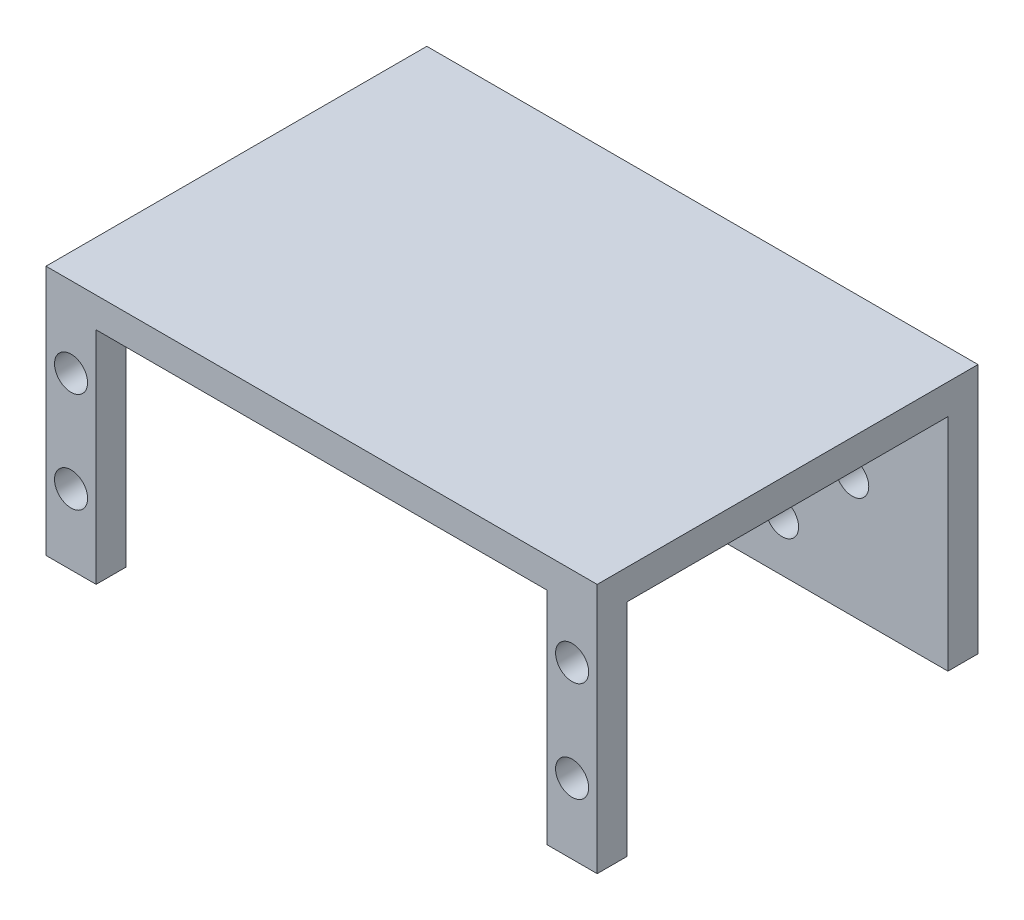
SolidWorks part; units mm, degrees
ref_plane "前视基准面" through (0, 0, 0) normal (0, 0, 1) x (1, 0, 0)
ref_plane "上视基准面" through (0, 0, 0) normal (0, 1, 0) x (1, 0, 0)
ref_plane "右视基准面" through (0, 0, 0) normal (1, 0, 0) x (0, 0, -1)
sketch "草图1" plane through (0, 0, 0) normal (0, 0, 1) x (1, 0, 0)
  line L1 (-27.5, -12.5) -> (27.5, -12.5)
  line L2 (-27.5, -12.5) -> (-27.5, 12.5)
  line L3 (-27.5, 12.5) -> (27.5, 12.5)
  line L4 (27.5, -12.5) -> (27.5, 12.5)
  line L5 (-27.5, -12.5) -> (27.5, 12.5) construction
  line L6 (-27.5, 12.5) -> (27.5, -12.5) construction
  point P0 (0, 0)
  dimension "D1" = 55
  dimension "D2" = 25
extrude "凸台-拉伸1" add sketch "草图1" along normal blind 3
sketch "草图2" plane through (0, 0, 3) normal (0, 0, 1) x (1, 0, 0)
  line L0 (27.5, -12.5) -> (27.5, 12.5) construction
  line L1 (-27.5, 12.5) -> (27.5, 12.5)
  line L2 (-27.5, 12.5) -> (-27.5, 9.5)
  line L3 (-27.5, 9.5) -> (27.5, 9.5)
  line L4 (27.5, 12.5) -> (27.5, 9.5)
  dimension "D1" = 3
extrude "凸台-拉伸2" add sketch "草图2" along normal blind 35
sketch "草图3" plane through (0, 9.5, 0) normal (0, -1, 0) x (1, 0, 0)
  line L1 (-27.5, 38) -> (-22.5, 38)
  line L2 (-27.5, 38) -> (-27.5, 35)
  line L3 (-27.5, 35) -> (-22.5, 35)
  line L4 (-22.5, 38) -> (-22.5, 35)
  line L5 (27.5, 38) -> (22.5, 38)
  line L6 (27.5, 38) -> (27.5, 35)
  line L7 (27.5, 35) -> (22.5, 35)
  line L8 (22.5, 38) -> (22.5, 35)
  dimension "D1" = 5
  dimension "D2" = 5
  dimension "D3" = 3
  dimension "D4" = 3
extrude "凸台-拉伸3" add sketch "草图3" along normal blind 22
sketch "草图4" plane through (0, 0, 38) normal (0, 0, 1) x (1, 0, 0)
  line L0 (-25, -12.5) -> (-25, 12.5) construction
  line L1 (-22.5, -12.5) -> (-27.5, -12.5) construction
  line L2 (27.5, 12.5) -> (-27.5, 12.5) construction
  line L3 (-22.5, 9.5) -> (22.5, 9.5) construction
  line L4 (0, 12.5) -> (0, 9.5) construction
  line L5 (-27.5, 9.5) -> (27.5, 9.5) construction
  circle A0 centre (-25, -5.5) radius 1.65
  circle A1 centre (-25, 4.5) radius 1.65
  circle A2 centre (25, 4.5) radius 1.65
  circle A3 centre (25, -5.5) radius 1.65
  dimension "D1" = 3.3
  dimension "D2" = 3.3
  dimension "D3" = 5
  dimension "D4" = 10
extrude "切除-拉伸1" cut sketch "草图4" against normal up to next
sketch "草图7" plane through (0, 0, 3) normal (0, 0, 1) x (1, 0, 0)
  line L0 (0, -0.5) -> (27.5, -0.5) construction
  line L1 (27.5, -12.5) -> (27.5, 12.5) construction
  line L2 (10.95, -12.5) -> (10.95, 12.5) construction
  line L3 (-27.5, -12.5) -> (27.5, -12.5) construction
  line L4 (27.5, 12.5) -> (-27.5, 12.5) construction
  circle A0 centre (17.95, -0.5) radius 1.65
  circle A1 centre (10.95, 6.5) radius 1.65
  circle A2 centre (3.95, -0.5) radius 1.65
  circle A3 centre (10.95, -7.5) radius 1.65
  point P19 (0, 0)
  point P20 (-34.0527, -0.4183)
  point P21 (-34.3874, -5.6057)
  dimension "D2" = 3.3
  dimension "D3" = 3.3
  dimension "D4" = 3.3
  dimension "D5" = 3.3
  dimension "D1" = 16.55
  dimension "D6" = 7
  dimension "D7" = 7
  dimension "D8" = 7
  dimension "D9" = 7
  dimension "D10" = 13
extrude "切除-拉伸2" cut sketch "草图7" against normal blind 20
